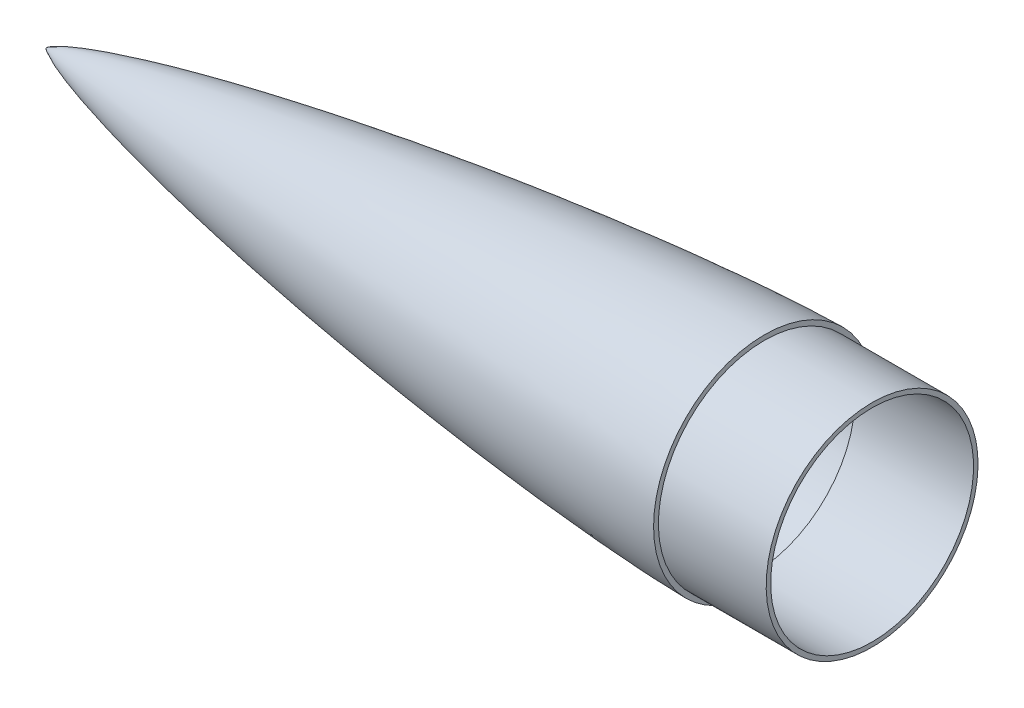
SolidWorks part; units mm, degrees
ref_plane "Front Plane" through (0, 0, 0) normal (0, 0, 1) x (1, 0, 0)
ref_plane "Top Plane" through (0, 0, 0) normal (0, 1, 0) x (1, 0, 0)
ref_plane "Right Plane" through (0, 0, 0) normal (1, 0, 0) x (0, 0, -1)
sketch "Sketch8" plane through (0, 0, 0) normal (0, 0, 1) x (1, 0, 0)
  line L1 (508, 0) -> (508, 78.359) construction
  line L4 (500.38, 74.93) -> (500.38, 71.755)
  line L5 (500.38, 71.755) -> (584.2, 71.755)
  line L6 (584.2, 71.755) -> (584.2, 74.93)
  line L7 (584.2, 74.93) -> (508, 74.93)
  line L8 (508, 78.359) -> (508, 74.93)
  line L9 (6.35, 0) -> (0, 0)
  line L10 (508, 0) -> (6.35, 0) construction
  spline S0 degree 4 poles (0, 0) (0.0028, 0.0112) (0.0101, 0.033) (0.0315, 0.074) (0.0698, 0.1316) (0.1192, 0.1954) (0.1898, 0.2761) (0.2748, 0.3639) (0.4019, 0.4843) (0.6026, 0.6567) (0.9144, 0.8984) (1.4448, 1.2671) (2.3422, 1.8219) (3.9262, 2.6864) (6.7922, 4.0534) (11.8911, 6.1625) (20.4311, 9.2161) (31.8916, 12.777) (45.6257, 16.595) (64.7152, 21.4391) (87.8428, 26.7555) (115.2609, 32.4758) (146.9821, 38.4855) (178.7896, 44.0179) (210.6663, 49.1356) (242.6009, 53.8775) (274.5859, 58.2664) (306.6159, 62.3133) (338.6872, 66.0193) (370.7971, 69.3748) (402.9439, 72.3578) (431.1037, 74.6062) (455.263, 76.2292) (474.4437, 77.278) (487.1031, 77.8359) (497.2672, 78.1744) (503.3998, 78.31) (506.4665, 78.3534) (508, 78.359) knots 0 0 0 0 0 0.000089 0.000179 0.000357 0.000536 0.000714 0.001009 0.001304 0.001892 0.002764 0.004066 0.006308 0.010067 0.016745 0.028668 0.049063 0.080344 0.109747 0.139151 0.201713 0.264275 0.326836 0.389398 0.45196 0.514521 0.577083 0.639645 0.702206 0.764768 0.82733 0.889891 0.921172 0.952453 0.976227 0.988113 1 1 1 1 1 construction
  spline S1 degree 4 poles (0, 0) (0.0028, 0.0112) (0.0101, 0.033) (0.0315, 0.074) (0.0698, 0.1316) (0.1192, 0.1954) (0.1898, 0.2761) (0.2748, 0.3639) (0.4019, 0.4843) (0.6026, 0.6567) (0.9144, 0.8984) (1.4448, 1.2671) (2.3422, 1.8219) (3.9262, 2.6864) (6.7922, 4.0534) (11.8911, 6.1625) (20.4311, 9.2161) (31.8916, 12.777) (45.6257, 16.595) (64.7152, 21.4391) (87.8428, 26.7555) (115.2609, 32.4758) (146.9821, 38.4855) (178.7896, 44.0179) (210.6663, 49.1356) (242.6009, 53.8775) (274.5859, 58.2664) (306.6159, 62.3133) (338.6872, 66.0193) (370.7971, 69.3748) (402.9439, 72.3578) (431.1037, 74.6062) (455.263, 76.2292) (474.4437, 77.278) (487.1031, 77.8359) (497.2672, 78.1744) (503.3998, 78.31) (506.4665, 78.3534) (508, 78.359) knots 0 0 0 0 0 0.000089 0.000179 0.000357 0.000536 0.000714 0.001009 0.001304 0.001892 0.002764 0.004066 0.006308 0.010067 0.016745 0.028668 0.049063 0.080344 0.109747 0.139151 0.201713 0.264275 0.326836 0.389398 0.45196 0.514521 0.577083 0.639645 0.702206 0.764768 0.82733 0.889891 0.921172 0.952453 0.976227 0.988113 1 1 1 1 1
  spline S3 degree 3 poles (6.35, 0) (8.89, 0.9418) (14.0024, 2.7022) (24.4137, 5.965) (37.5741, 9.6659) (53.502, 13.736) (74.8515, 18.791) (101.687, 24.5669) (134.0328, 30.8803) (166.4816, 36.6971) (209.8517, 43.8893) (264.2232, 51.9421) (329.6547, 60.2836) (384.3074, 66.1447) (428.093, 70.1028) (460.9625, 72.6562) (485.0617, 74.1685) (498.2051, 74.8262) (500.38, 74.93) knots 0.027272 0.027272 0.027272 0.027272 0.042373 0.057474 0.087677 0.117879 0.148081 0.208486 0.268891 0.329296 0.3897 0.51051 0.631319 0.752129 0.812534 0.872939 0.933343 0.945323 0.945323 0.945323 0.945323
  point P10 (499.4828, 75.184)
  point P13 (0, 0)
  dimension "D1" = 78.359
  dimension "D2" = 508
  dimension "D3" = 74.93
  dimension "D4" = 6.35
  dimension "D5" = 76.2
  dimension "D6" = 3.175
  dimension "D7" = 7.62
  dimension "D8" = 3.175
  dimension "D9" = 577.85
  dimension "D10" = 3.429
revolve "Revolve8" add sketch "Sketch8" angle 360 about L10
